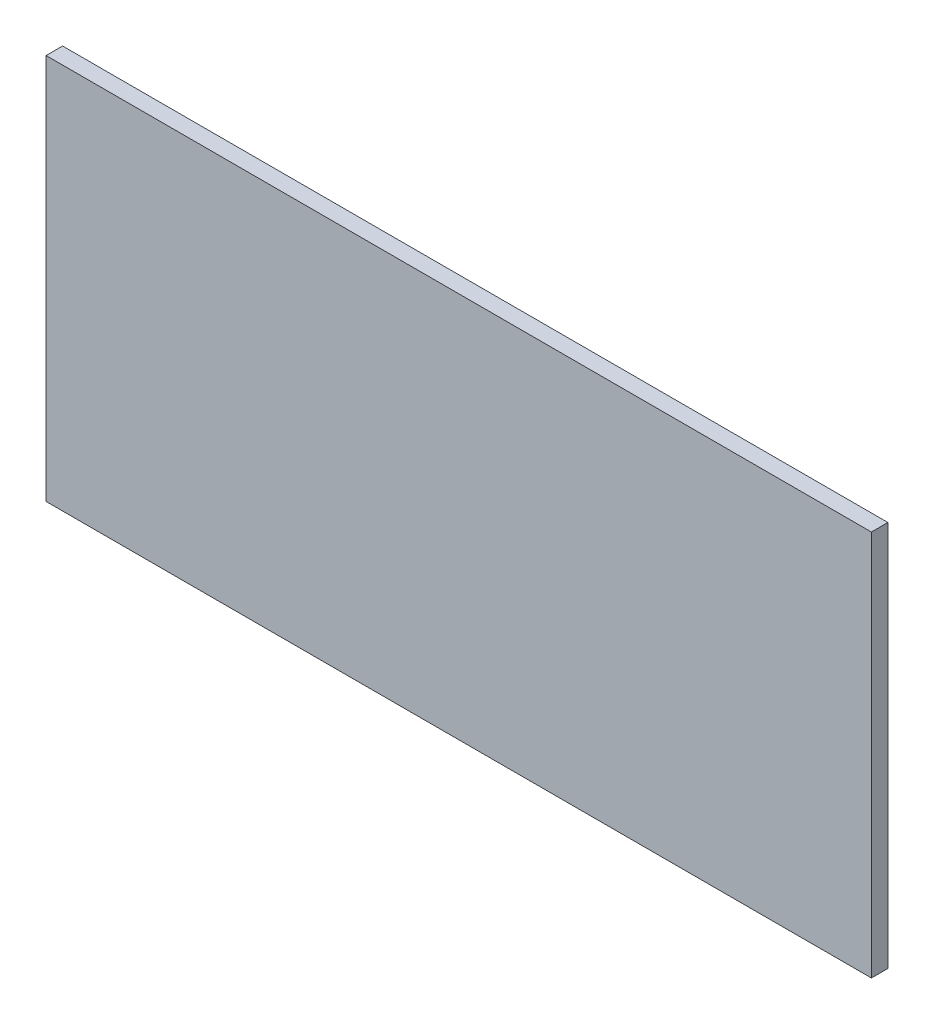
SolidWorks part; units mm, degrees
ref_plane "前视基准面" through (0, 0, 0) normal (0, 0, 1) x (1, 0, 0)
ref_plane "上视基准面" through (0, 0, 0) normal (0, 1, 0) x (1, 0, 0)
ref_plane "右视基准面" through (0, 0, 0) normal (1, 0, 0) x (0, 0, -1)
other "Configuration Table"
sketch "草图1" plane through (0, 0, 0) normal (0, 0, 1) x (1, 0, 0)
  line L9 (-50, 11.7) -> (0, 11.7)
  line L10 (-50, 11.7) -> (-50, -11.7)
  line L16 (-50, -11.7) -> (0, -11.7)
  line L17 (0, 11.7) -> (0, -11.7)
  dimension "D2" = 50
  dimension "D1" = 23.4
extrude "凸台-拉伸1" add sketch "草图1" along normal blind 1
